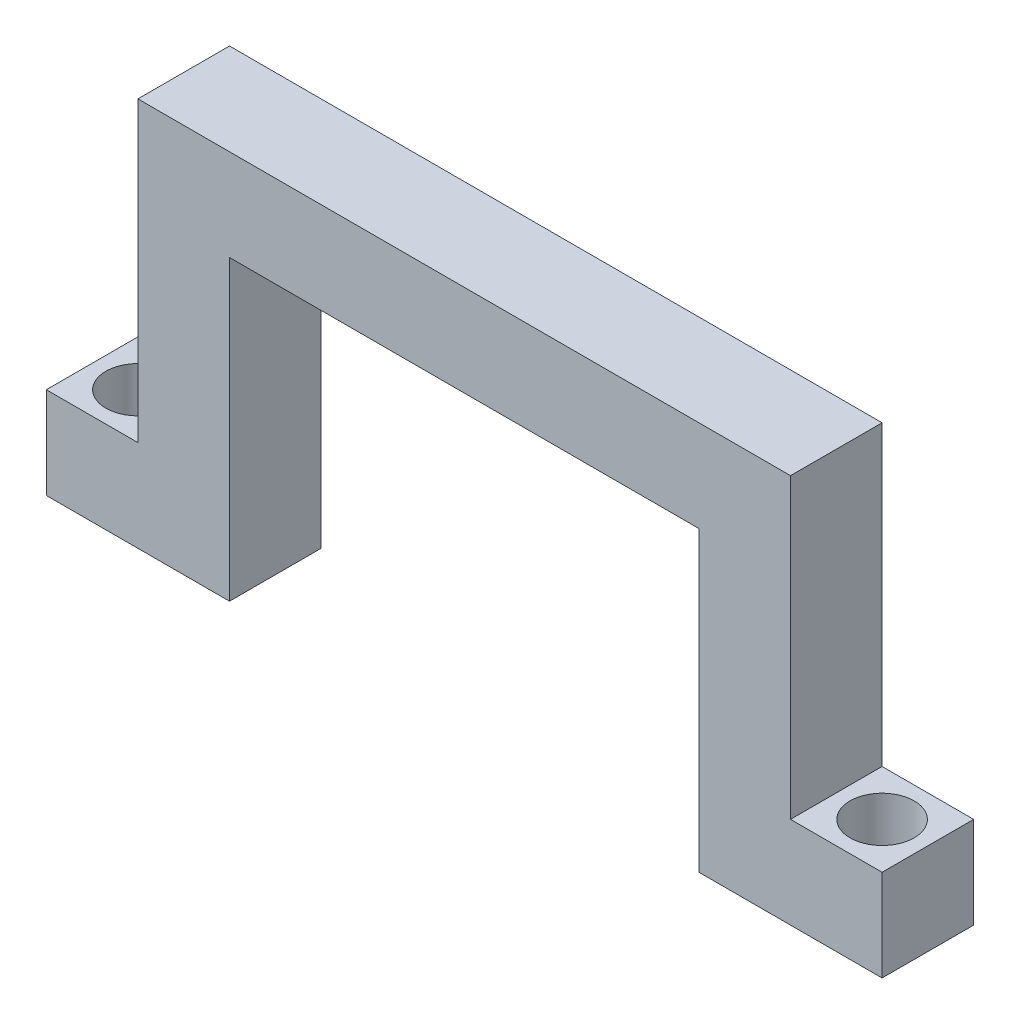
SolidWorks part; units mm, degrees
ref_plane "Front Plane" through (0, 0, 0) normal (0, 0, 1) x (1, 0, 0)
ref_plane "Top Plane" through (0, 0, 0) normal (0, 1, 0) x (1, 0, 0)
ref_plane "Right Plane" through (0, 0, 0) normal (1, 0, 0) x (0, 0, -1)
sketch "Sketch1" plane through (0, 0, 0) normal (0, 1, 0) x (1, 0, 0)
  line L1 (-22.7734, 0) -> (13.4216, 0)
  line L2 (-22.7734, 0) -> (-22.7734, -5.08)
  line L3 (-22.7734, -5.08) -> (13.4216, -5.08)
  line L4 (13.4216, 0) -> (13.4216, -5.08)
  dimension "D1" = 36.195
  dimension "D2" = 5.08
  dimension "D3" = 13.4216
extrude "Boss-Extrude1" add sketch "Sketch1" along normal blind 21.59
sketch "Sketch3" plane through (0, 0, 0) normal (0, 0, 1) x (1, 0, 0)
  line L0 (-22.7734, 0) -> (13.4216, 0) construction
  line L1 (-17.6934, 0) -> (8.3416, 0)
  line L2 (-17.6934, 0) -> (-17.6934, 16.51)
  line L3 (-17.6934, 16.51) -> (8.3416, 16.51)
  line L4 (8.3416, 0) -> (8.3416, 16.51)
  line L5 (-22.7734, 21.59) -> (-22.7734, 0) construction
  line L6 (13.4216, 21.59) -> (13.4216, 0) construction
  line L7 (-22.7734, 21.59) -> (13.4216, 21.59) construction
  dimension "D1" = 5.08
  dimension "D2" = 5.08
  dimension "D3" = 5.08
extrude "Cut-Extrude1" cut sketch "Sketch3" along normal blind 16.51 contours L2 L1 L4 L3
sketch "Sketch5" plane through (0, 0, 0) normal (0, 1, 0) x (1, 0, 0)
  line L0 (-4.6759, 0) -> (-4.6759, -8.6984) construction
  line L1 (-22.7734, 0) -> (-27.8534, 0)
  line L2 (-22.7734, 0) -> (-22.7734, -5.08)
  line L3 (-22.7734, -5.08) -> (-27.8534, -5.08)
  line L4 (-27.8534, 0) -> (-27.8534, -5.08)
  line L5 (13.4216, 0) -> (-22.7734, 0) construction
  line L6 (13.4216, 0) -> (18.5016, 0)
  line L7 (13.4216, 0) -> (13.4216, -5.08)
  line L8 (13.4216, -5.08) -> (18.5016, -5.08)
  line L9 (18.5016, 0) -> (18.5016, -5.08)
  dimension "D2" = 5.08
extrude "Boss-Extrude2" add sketch "Sketch5" along normal blind 5.08 contours L2 L1 L4 L3 | L6 L9 L8 L7
sketch "Sketch6" plane through (0, 0, 0) normal (0, 1, 0) x (1, 0, 0)
  line L0 (-22.7734, 0) -> (-27.8534, 0) construction
  line L1 (-22.7734, 0) -> (-22.7734, -5.08) construction
  line L2 (-4.6759, 0) -> (-4.6759, -10.1447) construction
  line L3 (13.4216, 0) -> (-22.7734, 0) construction
  circle A0 centre (-25.3134, -2.54) radius 1.778
  circle A1 centre (15.9616, -2.54) radius 1.778
  point P4 (-25.3134, 0)
  point P7 (-22.7734, -2.54)
  dimension "D1" = 3.556
extrude "Cut-Extrude2" cut sketch "Sketch6" along normal blind 9.144
